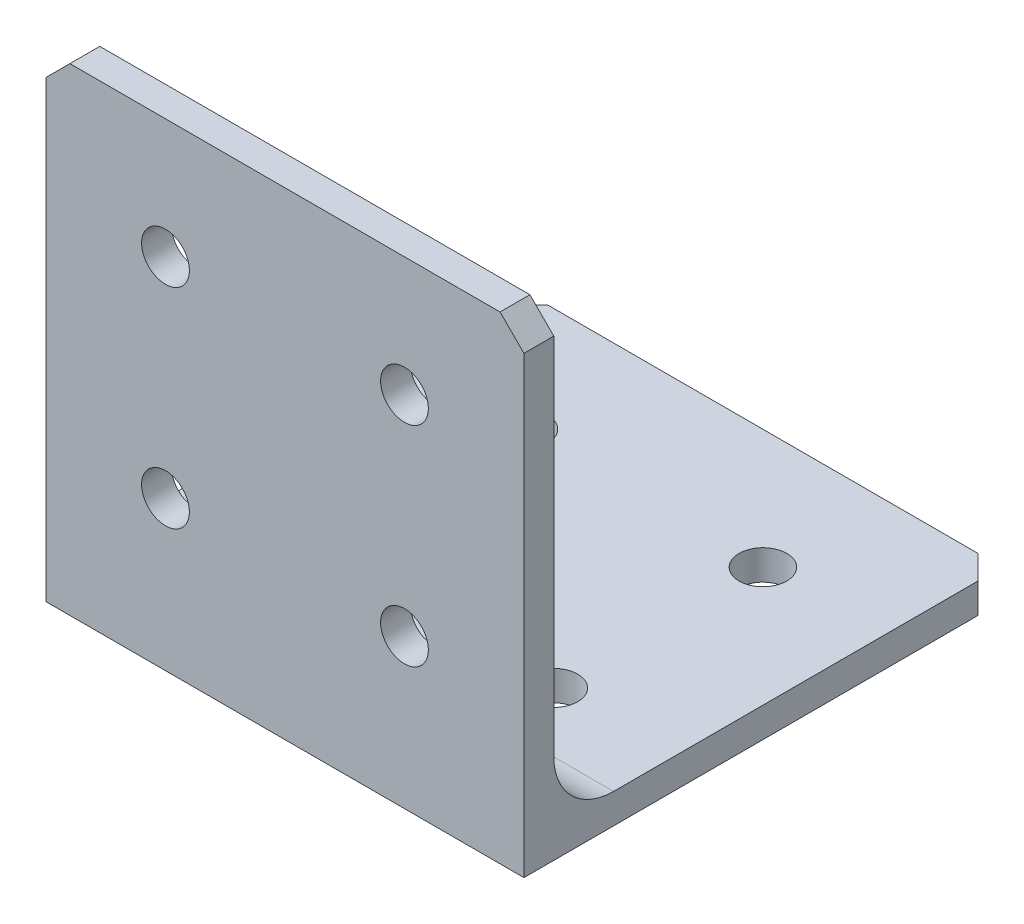
SolidWorks part; units mm, degrees
ref_plane "Front Plane" through (0, 0, 0) normal (0, 0, 1) x (1, 0, 0)
ref_plane "Top Plane" through (0, 0, 0) normal (0, 1, 0) x (1, 0, 0)
ref_plane "Right Plane" through (0, 0, 0) normal (1, 0, 0) x (0, 0, -1)
sketch "Sketch1" plane through (0, 0, 0) normal (1, 0, 0) x (0, 0, -1)
  line L0 (0, 0) -> (0, 50.8)
  line L1 (0, 50.8) -> (3.175, 50.8)
  line L2 (3.175, 50.8) -> (3.175, 3.175)
  line L3 (3.175, 3.175) -> (50.8, 3.175)
  line L4 (50.8, 3.175) -> (50.8, 0)
  line L5 (50.8, 0) -> (0, 0)
  dimension "D1" = 50.8
  dimension "D2" = 3.175
extrude "Boss-Extrude1" add sketch "Sketch1" along normal blind 50.8
sketch "Sketch2" plane through (0, 0, 0) normal (0, 0, 1) x (1, 0, 0)
  line L0 (0, 50.8) -> (0, 0) construction
  line L1 (50.8, 50.8) -> (50.8, 0) construction
  line L2 (50.8, 0) -> (0, 0) construction
  line L3 (50.8, 50.8) -> (0, 50.8) construction
  circle A0 centre (12.7, 38.1) radius 2.54
  circle A1 centre (12.7, 15.875) radius 2.54
  circle A2 centre (38.1, 38.1) radius 2.54
  circle A3 centre (38.1, 15.875) radius 2.54
  dimension "D1" = 5.08
  dimension "D2" = 12.7
  dimension "D3" = 12.7
  dimension "D4" = 15.875
  dimension "D5" = 12.7
extrude "Cut-Extrude1" cut sketch "Sketch2" against normal through all
sketch "Sketch3" plane through (0, 0, 0) normal (0, -1, 0) x (1, 0, 0)
  line L0 (50.8, -50.8) -> (0, -50.8) construction
  line L1 (50.8, 0) -> (0, 0) construction
  line L2 (50.8, 0) -> (50.8, -50.8) construction
  line L3 (0, 0) -> (0, -50.8) construction
  circle A0 centre (38.1, -38.1) radius 2.54
  circle A1 centre (38.1, -15.875) radius 2.54
  circle A2 centre (12.7, -38.1) radius 2.54
  circle A3 centre (12.7, -15.875) radius 2.54
  dimension "D1" = 5.08
  dimension "D2" = 12.7
  dimension "D3" = 15.875
  dimension "D4" = 12.7
  dimension "D5" = 12.7
extrude "Cut-Extrude2" cut sketch "Sketch3" against normal through all
fillet "Fillet1" radius 6.35 1 edges at (25.4, 3.175, -3.175)
chamfer "Chamfer1" distance 2.54 angle 45 4 edges at (50.8, 50.8, -1.5875) (0, 50.8, -1.5875) (50.8, 1.5875, -50.8) (0, 1.5875, -50.8)
